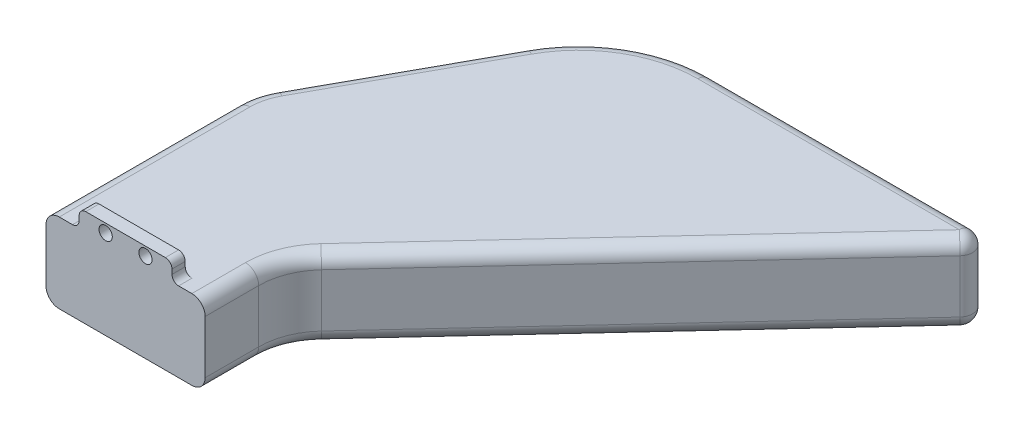
SolidWorks part; units mm, degrees
ref_plane "Front Plane" through (0, 0, 0) normal (0, 0, 1) x (1, 0, 0)
ref_plane "Top Plane" through (0, 0, 0) normal (0, 1, 0) x (1, 0, 0)
ref_plane "Right Plane" through (0, 0, 0) normal (1, 0, 0) x (0, 0, -1)
sketch "Sketch1" plane through (0, 0, 0) normal (0, 1, 0) x (1, 0, 0)
  line L0 (-30.6143, 0) -> (0, 0) construction
  line L1 (0, 0) -> (0, 18.9605) construction
  line L2 (-11.3817, 10.7916) -> (-4.7124, 22.9251)
  line L3 (0, 0) -> (30.6143, 0) construction
  line L4 (4.051, 28.1082) -> (23.7653, 28.1082)
  line L5 (24.4987, 26.4284) -> (1.3331, 1.4381)
  line L7 (-12, 8.3832) -> (-12, -6)
  line L8 (-12, -6) -> (0, -6)
  line L9 (0, -6) -> (0, -1.961)
  arc A0 (4.051, 28.1082) -> (-4.7124, 22.9251) centre (4.051, 18.1082) ccw
  arc A1 (24.4987, 26.4284) -> (23.7653, 28.1082) centre (23.7653, 27.1082) ccw
  arc A2 (1.3331, 1.4381) -> (0, -1.961) centre (5, -1.961) ccw
  arc A3 (-12, 8.3832) -> (-11.3817, 10.7916) centre (-7, 8.3832) cw
  point P19 (0, 0)
  dimension "D1" = 6
  dimension "D3" = 10
  dimension "D4" = 1
  dimension "D5" = 5
  dimension "D6" = 5
  dimension "D2" = 12
extrude "Boss-Extrude1" add sketch "Sketch1" along normal blind 6
fillet "Fillet1" radius 1 9 edges at (0, 6, 3.9805) (0.3452, 6, 0.1354) (12.9159, 6, -13.9333) (24.6818, 6, -27.5083) (13.9082, 6, -28.1082) (-1.0397, 6, -26.7154) (-8.0471, 6, -16.8584) (-11.843, 6, -9.6265) (-12, 6, -1.1916)
fillet "Fillet2" radius 1 9 edges at (-11.843, 0, -9.6265) (-8.0471, 0, -16.8584) (-1.0397, 0, -26.7154) (13.9082, 0, -28.1082) (24.6818, 0, -27.5083) (12.9159, 0, -13.9333) (0.3452, 0, 0.1354) (-12, 0, -1.1916) (0, 0, 3.9805)
ref_plane "Plane1" through (0, 0, 0) normal (0, 0, 1) x (1, 0, 0)
sketch "Sketch3" plane through (0, 0, 6) normal (0, 0, 1) x (1, 0, 0)
  line L0 (-6, 6) -> (-6, 10.8641) construction
  line L1 (-11, 6) -> (-1, 6) construction
  line L2 (-9.5, 6) -> (-9.5, 7.35)
  line L3 (-9.5, 7.35) -> (-2.5, 7.35)
  line L4 (-2.5, 6) -> (-2.5, 7.35)
  line L5 (-9.5, 6) -> (-2.5, 6)
  point P9 (-6, 7.35)
  dimension "D1" = 1.35
  dimension "D2" = 7
extrude "Boss-Extrude2" add sketch "Sketch3" against normal blind 1
fillet "Fillet4" radius 0.5 4 edges at (-9.5, 7.35, 5.5) (-9.5, 6, 5.5) (-2.5, 6, 5.5) (-2.5, 7.35, 5.5)
sketch "Sketch4" plane through (0, 0, 5) normal (0, 0, -1) x (-1, 0, 0)
  line L0 (6, 7.35) -> (6, 6) construction
  line L1 (3, 7.35) -> (9, 7.35) construction
  line L2 (10, 6) -> (2, 6) construction
  circle A0 centre (7.5, 6.7) radius 0.5
  circle A1 centre (4.5, 6.7) radius 0.5
  dimension "D1" = 1
  dimension "D2" = 1.5
  dimension "D3" = 0.7
extrude "Cut-Extrude1" cut sketch "Sketch4" against normal blind 1
